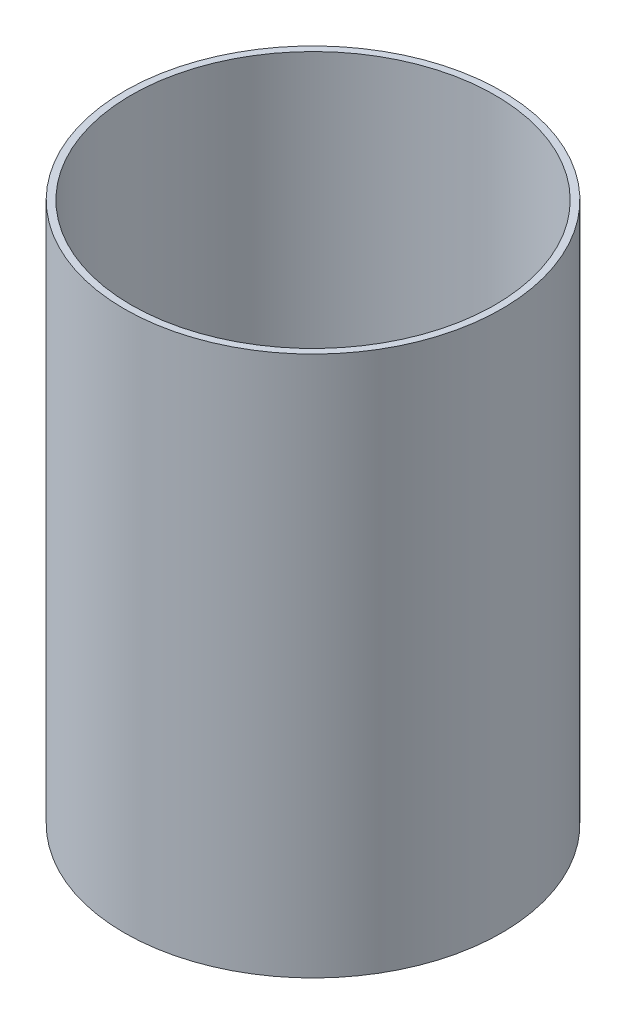
SolidWorks part; units mm, degrees
ref_plane "Front Plane" through (0, 0, 0) normal (0, 0, 1) x (1, 0, 0)
ref_plane "Top Plane" through (0, 0, 0) normal (0, 1, 0) x (1, 0, 0)
ref_plane "Right Plane" through (0, 0, 0) normal (1, 0, 0) x (0, 0, -1)
sketch "Sketch1" plane through (0, 0, 0) normal (0, 1, 0) x (1, 0, 0)
  circle A0 centre (0, 0) radius 69.85
  circle A1 centre (0, 0) radius 67.31
  dimension "D1" = 139.7
  dimension "D2" = 134.62
extrude "Boss-Extrude1" add sketch "Sketch1" along normal blind 200
